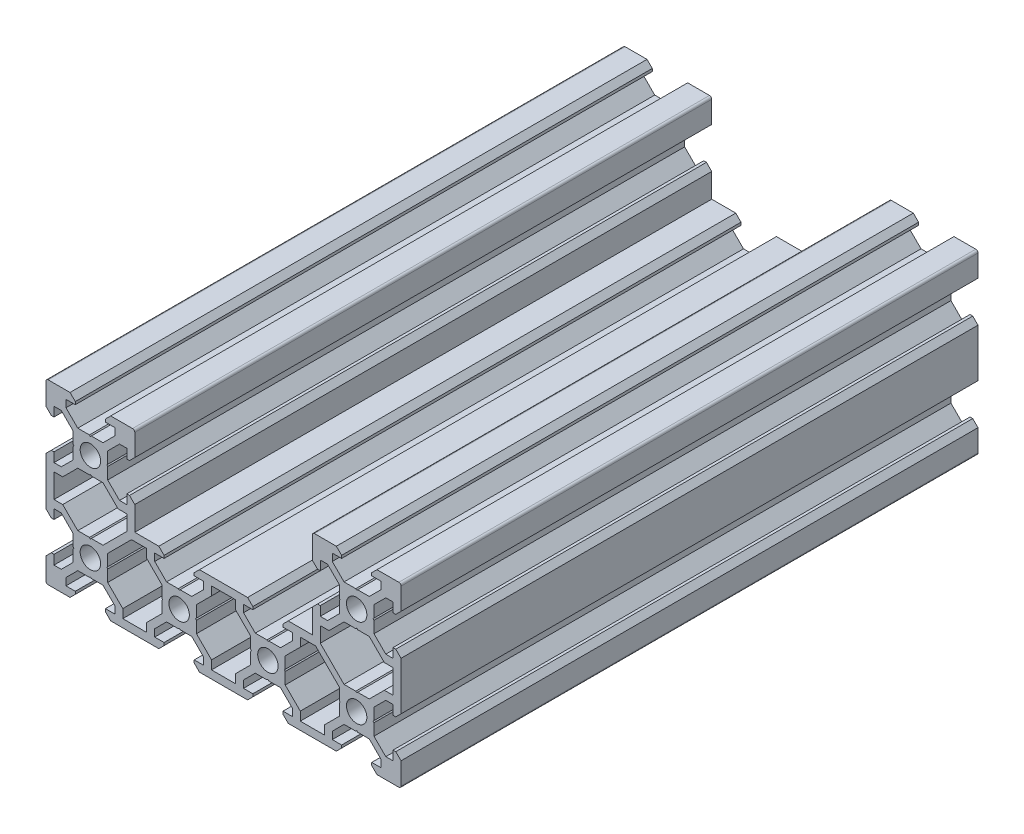
SolidWorks part; units mm, degrees
material "6063-T5"
ref_plane "Plan de face" through (0, 0, 0) normal (0, 0, 1) x (1, 0, 0)
ref_plane "Plan de dessus" through (0, 0, 0) normal (0, 1, 0) x (1, 0, 0)
ref_plane "Plan de droite" through (0, 0, 0) normal (1, 0, 0) x (0, 0, -1)
sketch "Esquisse1" plane through (0, 0, 0) normal (0, 0, 1) x (1, 0, 0)
  line L0 (-3.9, 2.8393) -> (-6.5607, 5.5)
  line L1 (-3.9, 3.9) -> (3.9, 3.9) construction
  line L2 (-3.9, 3.9) -> (-3.9, -3.9) construction
  line L3 (-3.9, -3.9) -> (3.9, -3.9) construction
  line L4 (3.9, 3.9) -> (3.9, -3.9) construction
  line L5 (-3.9, 3.9) -> (3.9, -3.9) construction
  line L6 (-3.9, -3.9) -> (3.9, 3.9) construction
  line L7 (-2.8393, 3.9) -> (-5.5, 6.5607)
  line L8 (-6.5607, 5.5) -> (-8.2, 5.5)
  line L9 (-8.2, 5.5) -> (-8.2, 3.395)
  line L10 (-8.2, 3.395) -> (-8.815, 3.395)
  line L11 (-8.815, 3.395) -> (-10, 4.58)
  line L12 (-10, 4.58) -> (-10, 9.5)
  line L13 (-4.58, 10) -> (-9.5, 10)
  line L14 (-3.395, 8.815) -> (-4.58, 10)
  line L15 (-3.395, 8.2) -> (-3.395, 8.815)
  line L16 (-5.5, 8.2) -> (-3.395, 8.2)
  line L17 (-5.5, 6.5607) -> (-5.5, 8.2)
  line L18 (0, 7.4695) -> (0, -30) construction
  line L19 (5.5, 6.5607) -> (5.5, 8.2)
  line L20 (5.5, 8.2) -> (3.395, 8.2)
  line L21 (3.395, 8.2) -> (3.395, 8.815)
  line L22 (3.395, 8.815) -> (4.58, 10)
  line L23 (4.58, 10) -> (9.5, 10)
  line L24 (10, 4.58) -> (10, 9.5)
  line L25 (8.815, 3.395) -> (10, 4.58)
  line L26 (8.2, 3.395) -> (8.815, 3.395)
  line L27 (8.2, 5.5) -> (8.2, 3.395)
  line L28 (6.5607, 5.5) -> (8.2, 5.5)
  line L29 (2.8393, 3.9) -> (5.5, 6.5607)
  line L30 (3.9, 2.8393) -> (6.5607, 5.5)
  line L31 (-2.8393, 3.9) -> (2.8393, 3.9)
  line L32 (-3.9, -2.8393) -> (-6.5607, -5.5)
  line L33 (-2.8393, -3.9) -> (-6.2393, -7.3)
  line L34 (-3.9, 2.8393) -> (-3.9, -2.8393)
  line L35 (-6.5607, -5.5) -> (-8.2, -5.5)
  line L36 (-8.2, -5.5) -> (-8.2, -3.395)
  line L37 (-8.2, -3.395) -> (-8.815, -3.395)
  line L38 (-8.815, -3.395) -> (-10, -4.58)
  line L39 (-10, -4.58) -> (-10, -15.42)
  line L40 (-6.2393, -7.3) -> (-8.2, -7.3)
  line L41 (-8.2, -7.3) -> (-8.2, -12.7)
  line L42 (30, -10) -> (-10, -10) construction
  line L43 (6.2393, -7.3) -> (8.2, -7.3)
  line L44 (8.2, -7.3) -> (8.2, -10.7393)
  line L45 (8.815, -3.395) -> (10, -4.58)
  line L46 (8.2, -3.395) -> (8.815, -3.395)
  line L47 (8.2, -5.5) -> (8.2, -3.395)
  line L48 (6.5607, -5.5) -> (8.2, -5.5)
  line L49 (2.8393, -3.9) -> (6.2393, -7.3)
  line L50 (3.9, -2.8393) -> (6.5607, -5.5)
  line L51 (30, 10) -> (-10, -30) construction
  line L52 (-2.8393, -3.9) -> (2.8393, -3.9)
  line L53 (3.9, 2.8393) -> (3.9, -2.8393)
  line L54 (-3.9, -16.1) -> (3.9, -23.9) construction
  line L55 (-3.9, -23.9) -> (3.9, -16.1) construction
  line L56 (-3.9, -23.9) -> (3.9, -23.9) construction
  line L57 (-3.9, -16.1) -> (3.9, -16.1) construction
  line L58 (-3.9, -23.9) -> (-3.9, -16.1) construction
  line L59 (3.9, -23.9) -> (3.9, -16.1) construction
  line L60 (16.1, -23.9) -> (23.9, -16.1) construction
  line L61 (-2.8393, -16.1) -> (2.8393, -16.1)
  line L62 (-6.2393, -12.7) -> (-8.2, -12.7)
  line L63 (-8.815, -16.605) -> (-10, -15.42)
  line L64 (-8.2, -16.605) -> (-8.815, -16.605)
  line L65 (-8.2, -14.5) -> (-8.2, -16.605)
  line L66 (-6.5607, -14.5) -> (-8.2, -14.5)
  line L67 (-3.9, -22.8393) -> (-3.9, -17.1607)
  line L68 (-2.8393, -16.1) -> (-6.2393, -12.7)
  line L69 (-3.9, -17.1607) -> (-6.5607, -14.5)
  line L70 (23.9, -23.9) -> (16.1, -16.1) construction
  line L71 (23.9, -16.1) -> (16.1, -16.1) construction
  line L72 (16.1, -23.9) -> (16.1, -16.1) construction
  line L73 (23.9, -23.9) -> (16.1, -23.9) construction
  line L74 (23.9, -23.9) -> (23.9, -16.1) construction
  line L75 (10, -4.58) -> (10, -10)
  line L76 (-2.8393, -23.9) -> (-5.5, -26.5607)
  line L77 (-10, -24.58) -> (-10, -29.5)
  line L78 (-8.815, -23.395) -> (-10, -24.58)
  line L79 (-8.2, -23.395) -> (-8.815, -23.395)
  line L80 (-8.2, -25.5) -> (-8.2, -23.395)
  line L81 (-6.5607, -25.5) -> (-8.2, -25.5)
  line L82 (-5.5, -26.5607) -> (-5.5, -28.2)
  line L83 (-3.9, -22.8393) -> (-6.5607, -25.5)
  line L84 (-5.5, -28.2) -> (-3.395, -28.2)
  line L85 (-3.395, -28.2) -> (-3.395, -28.815)
  line L86 (-3.395, -28.815) -> (-4.58, -30)
  line L87 (-4.58, -30) -> (-9.5, -30)
  line L88 (15.42, -10) -> (10, -10)
  line L89 (2.8393, -23.9) -> (5.5, -26.5607)
  line L90 (3.9, -22.8393) -> (7.3, -26.2393)
  line L91 (-2.8393, -23.9) -> (2.8393, -23.9)
  line L92 (30, -10) -> (30, -30) construction
  line L93 (5.5, -26.5607) -> (5.5, -28.2)
  line L94 (5.5, -28.2) -> (3.395, -28.2)
  line L95 (3.395, -28.2) -> (3.395, -28.815)
  line L96 (3.395, -28.815) -> (4.58, -30)
  line L97 (7.3, -26.2393) -> (7.3, -28.2)
  line L98 (3.9, -22.8393) -> (3.9, -17.1607)
  line L99 (22.8393, -16.1) -> (17.1607, -16.1)
  line L100 (16.1, -22.8393) -> (16.1, -17.1607)
  line L101 (17.1607, -16.1) -> (14.5, -13.4393)
  line L102 (16.1, -17.1607) -> (12.7, -13.7607)
  line L103 (14.5, -13.4393) -> (14.5, -11.8)
  line L104 (14.5, -11.8) -> (16.605, -11.8)
  line L105 (16.605, -11.8) -> (16.605, -11.185)
  line L106 (16.605, -11.185) -> (15.42, -10)
  line L107 (12.7, -11.8) -> (9.2607, -11.8)
  line L108 (12.7, -13.7607) -> (12.7, -11.8)
  line L109 (12.7, -28.2) -> (7.3, -28.2)
  line L110 (12.7, -26.2393) -> (12.7, -28.2)
  line L111 (15.42, -30) -> (4.58, -30)
  line L112 (16.605, -28.815) -> (15.42, -30)
  line L113 (16.605, -28.2) -> (16.605, -28.815)
  line L114 (14.5, -28.2) -> (16.605, -28.2)
  line L115 (14.5, -26.5607) -> (14.5, -28.2)
  line L116 (22.8393, -23.9) -> (17.1607, -23.9)
  line L117 (16.1, -22.8393) -> (12.7, -26.2393)
  line L118 (17.1607, -23.9) -> (14.5, -26.5607)
  line L119 (23.9, -22.8393) -> (23.9, -17.1607)
  line L120 (22.8393, -16.1) -> (25.5, -13.4393)
  line L121 (23.9, -17.1607) -> (27.3, -13.7607)
  line L122 (23.395, -11.8) -> (25.5, -11.8)
  line L123 (25.5, -11.8) -> (25.5, -13.4393)
  line L124 (23.395, -11.8) -> (23.395, -11.185)
  line L125 (23.395, -11.185) -> (24.58, -10)
  line L126 (24.58, -10) -> (30, -10)
  line L127 (27.3, -13.7607) -> (27.3, -11.8)
  line L128 (27.3, -11.8) -> (30, -11.8)
  line L129 (23.9, -22.8393) -> (27.3, -26.2393)
  line L130 (27.3, -26.2393) -> (27.3, -28.2)
  line L131 (27.3, -28.2) -> (30, -28.2)
  line L132 (20, -16.1) -> (20, -23.9) construction
  line L133 (10, -28.2) -> (10, -10) construction
  line L134 (30, -10) -> (30, -11.8)
  line L135 (30, -28.2) -> (30, -30)
  line L136 (2.8393, -16.1) -> (8.2, -10.7393)
  line L137 (24.58, -30) -> (30, -30)
  line L138 (23.395, -28.815) -> (24.58, -30)
  line L139 (23.395, -28.2) -> (23.395, -28.815)
  line L140 (25.5, -28.2) -> (23.395, -28.2)
  line L141 (25.5, -26.5607) -> (25.5, -28.2)
  line L142 (3.9, -17.1607) -> (9.2607, -11.8)
  line L143 (22.8393, -23.9) -> (25.5, -26.5607)
  circle A0 centre (0, 0) radius 2.3
  arc A1 (-10, 9.5) -> (-9.5, 10) centre (-9.5, 9.5) cw
  arc A2 (10, 9.5) -> (9.5, 10) centre (9.5, 9.5) ccw
  arc A3 (-10, -29.5) -> (-9.5, -30) centre (-9.5, -29.5) ccw
  circle A4 centre (0, -20) radius 2.3
  circle A7 centre (20, -20) radius 2.3
  point P62 (10, -10)
  point P78 (-8.2, -10)
  point P94 (10, -10)
  point P162 (10, -28.2)
  dimension "D1" = 4.6
  dimension "D3" = 0.5
  dimension "D2" = 1.5
  dimension "D4" = 20
  dimension "D5" = 11
  dimension "D6" = 9.16
  dimension "D7" = 6.79
  dimension "D8" = 1.8
  dimension "D9" = 4.3
  dimension "D10" = 1.5
  dimension "D11" = 6.79
  dimension "D15" = 1.8
extrude "Boss.-Extru.1" add sketch "Esquisse1" along normal blind 130
sketch "Esquisse2" plane through (0, 0, 130) normal (0, 0, 1) x (1, 0, 0)
  line L0 (0, 3.9) -> (0, -23.9) construction
  line L1 (2.8393, 3.9) -> (-2.8393, 3.9) construction
  line L2 (-2.8393, -23.9) -> (2.8393, -23.9) construction
  line L3 (-10, -10) -> (30, -10) construction
  line L4 (-10, -4.58) -> (-10, -15.42) construction
  line L5 (-0.21, 3.9) -> (0, 3.69)
  line L6 (0.21, 3.9) -> (0, 3.69)
  line L7 (-0.21, 3.9) -> (0.21, 3.9)
  line L8 (-3.9, 0) -> (3.9, 0) construction
  line L9 (-3.9, 2.8393) -> (-3.9, -2.8393) construction
  line L10 (3.9, -2.8393) -> (3.9, 2.8393) construction
  line L11 (9.8536, 9.8536) -> (-10, -10) construction
  line L12 (3.9, -0.21) -> (3.9, 0.21)
  line L13 (3.9, 0.21) -> (3.69, 0)
  line L14 (3.9, -0.21) -> (3.69, 0)
  line L15 (-9.8536, 9.8536) -> (10, -10) construction
  line L16 (0.21, -3.9) -> (0, -3.69)
  line L17 (-0.21, -3.9) -> (0, -3.69)
  line L18 (0.21, -3.9) -> (-0.21, -3.9)
  line L19 (-3.9, 0.21) -> (-3.9, -0.21)
  line L20 (-3.9, -0.21) -> (-3.69, 0)
  line L21 (-3.9, 0.21) -> (-3.69, 0)
  line L22 (-3.9, -20.21) -> (-3.69, -20)
  line L23 (-3.9, -19.79) -> (-3.69, -20)
  line L24 (-3.9, -20.21) -> (-3.9, -19.79)
  line L25 (0.21, -16.1) -> (-0.21, -16.1)
  line L26 (-0.21, -16.1) -> (0, -16.31)
  line L27 (0.21, -16.1) -> (0, -16.31)
  line L28 (3.9, -19.79) -> (3.69, -20)
  line L29 (3.9, -20.21) -> (3.69, -20)
  line L30 (3.9, -19.79) -> (3.9, -20.21)
  line L31 (-0.21, -23.9) -> (0.21, -23.9)
  line L32 (0.21, -23.9) -> (0, -23.69)
  line L33 (-0.21, -23.9) -> (0, -23.69)
  line L34 (10, -10) -> (10, -30) construction
  line L35 (4.58, -30) -> (15.42, -30) construction
  line L36 (20.21, -23.9) -> (20, -23.69)
  line L37 (19.79, -23.9) -> (20, -23.69)
  line L38 (20.21, -23.9) -> (19.79, -23.9)
  line L39 (16.1, -19.79) -> (16.1, -20.21)
  line L40 (16.1, -20.21) -> (16.31, -20)
  line L41 (16.1, -19.79) -> (16.31, -20)
  line L42 (19.79, -16.1) -> (20, -16.31)
  line L43 (20.21, -16.1) -> (20, -16.31)
  line L44 (19.79, -16.1) -> (20.21, -16.1)
  line L45 (23.9, -20.21) -> (23.9, -19.79)
  line L46 (23.9, -19.79) -> (23.69, -20)
  line L47 (23.9, -20.21) -> (23.69, -20)
  arc A0 (10, 9.5) -> (9.5, 10) centre (9.5, 9.5) ccw construction
  arc A1 (-9.5, 10) -> (-10, 9.5) centre (-9.5, 9.5) ccw construction
  dimension "D1" = 45
  dimension "D2" = 0.42
extrude "Enlèv. mat.-Extru.1" cut sketch "Esquisse2" against normal through all
mirror "Symétrie1" about plane through (30, -10, 130) normal (-1, 0, 0) of "Enlèv. mat.-Extru.1", "Boss.-Extru.1"
